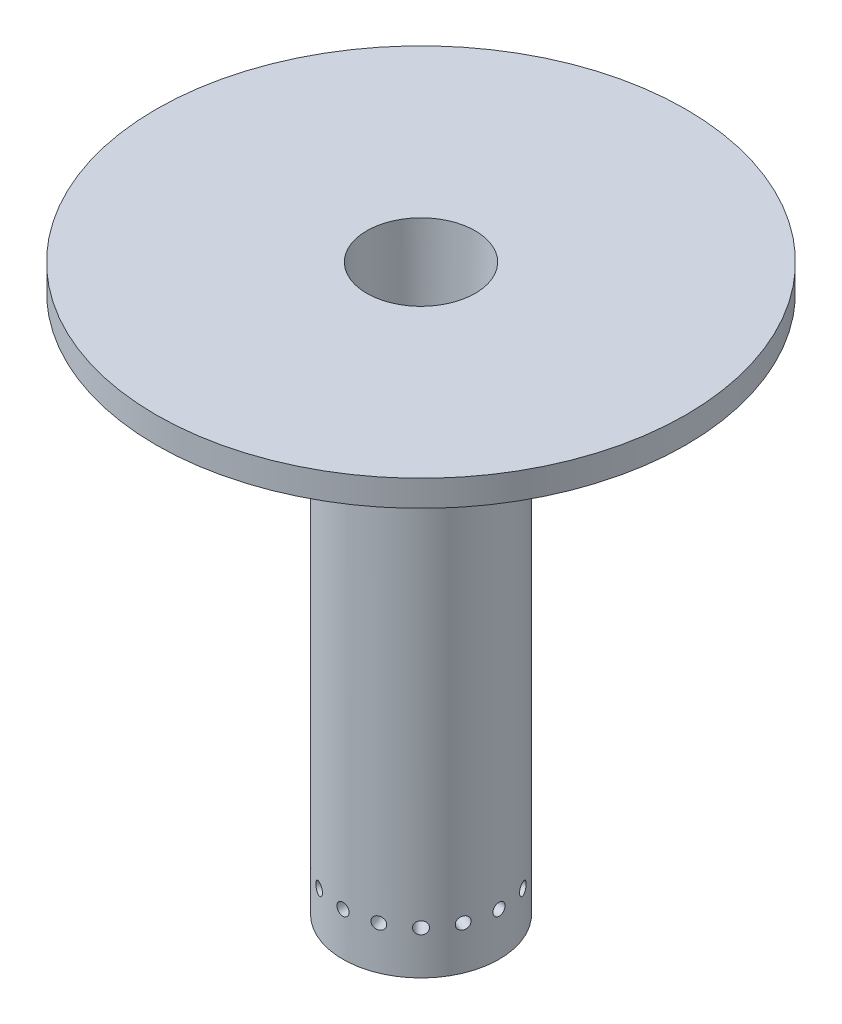
SolidWorks part; units mm, degrees
ref_plane "Front Plane" through (0, 0, 0) normal (0, 0, 1) x (1, 0, 0)
ref_plane "Top Plane" through (0, 0, 0) normal (0, 1, 0) x (1, 0, 0)
ref_plane "Right Plane" through (0, 0, 0) normal (1, 0, 0) x (0, 0, -1)
sketch "Sketch1" plane through (0, 0, 0) normal (0, 0, 1) x (1, 0, 0)
  line L0 (0, 0) -> (-30.48, 0)
  line L1 (-30.48, 0) -> (-30.48, -3)
  line L2 (-30.48, -3) -> (-17.78, -3)
  line L3 (-17.78, -3) -> (-17.78, -8)
  line L4 (-17.78, -8) -> (-9, -8)
  line L5 (-9, -8) -> (-9, -65)
  line L6 (-9, -65) -> (0, -65)
  line L7 (0, -65) -> (0, 0)
  dimension "D1" = 30.48
  dimension "D2" = 12.7
  dimension "D3" = 5
  dimension "D4" = 65
  dimension "D5" = 3
  dimension "D6" = 9
revolve "Revolve1" add sketch "Sketch1" angle 360 about L7
hole_wizard "1/4 NPT Tapped Hole1" positions "Sketch2" profile "Sketch4" size "1/4" standard "ANSI Inch"
sketch "Sketch2" plane through (0, 0, 0) normal (0, 1, 0) x (1, 0, 0)
  point P0 (0, 0)
sketch "Sketch4" plane through (0, 0, 0) normal (1, 0, 0) x (0, 0, 1)
  line L0 (0, 0) -> (0, 40.4123)
  line L1 (5.5626, 37.07) -> (0, 40.4123)
  line L2 (-5.5626, 37.07) -> (0, 40.4123) construction
  line L3 (5.5626, 37.07) -> (5.5626, 10.02)
  line L4 (5.5626, 10.02) -> (5.9437, 10.02)
  line L5 (5.9437, 10.02) -> (6.2437, 0)
  line L6 (-5.9437, 10.02) -> (-6.2437, 0) construction
  line L7 (6.2437, 0) -> (0, 0)
  line L8 (0, -6.35) -> (0, 107.95) construction
  line L11 (-5.5626, 10.02) -> (-5.9437, 10.02) construction
  dimension "Tap Drill Dia." = 11.1252
  dimension "Tap Drill Depth" = 37.07
  dimension "Thread Dia." = 12.4874
  dimension "Thread Angle" = 3.43
  dimension "Thread Depth" = 10.02
  dimension "Drill Angle" = 118
cosmetic thread "Hole Thread1" parameters "D1"=10.02, "D2"=13.716
hole_wizard "3/8 (0.375) Diameter Hole1" positions "Sketch6" profile "Sketch7" hole size "3/8" standard "ANSI Inch"
sketch "Sketch6" plane through (0, 0, 0) normal (0, 1, 0) x (1, 0, 0)
  point P0 (0, 0)
sketch "Sketch7" plane through (0, 0, 0) normal (1, 0, 0) x (0, 0, 1)
  line L0 (0, 0) -> (0, 63.8616)
  line L1 (0, 63.8616) -> (4.7625, 61)
  line L2 (4.7625, 61) -> (4.7625, 0)
  line L5 (4.7625, 0) -> (0, 0)
  line L10 (0, 63.8616) -> (-4.7625, 61) construction
  line L11 (0, -6.35) -> (0, 107.95) construction
  dimension "Hole Dia." = 9.525
  dimension "Hole Depth" = 61
  dimension "Drill Angle" = 118
ref_plane "Plane1" through (0, 0, 9) normal (0, 0, 1) x (1, 0, 0)
hole_wizard "#54 (0.055) Diameter Hole1" positions "Sketch9" profile "Sketch10" hole size "#54" standard "ANSI Inch"
sketch "Sketch9" plane through (0, 0, 9) normal (0, 0, 1) x (1, 0, 0)
  line L1 (30.48, 0) -> (-30.48, 0) construction
  point P0 (0, -60)
  dimension "D1" = 60
sketch "Sketch10" plane through (0, -60, 9) normal (1, 0, 0) x (0, -1, 0)
  line L0 (0, 0) -> (0, 4.2375)
  line L1 (0, 4.2375) -> (0.6985, 4.2375)
  line L2 (0.6985, 4.2375) -> (0.6985, 0)
  line L5 (0.6985, 0) -> (0, 0)
  line L11 (0, -6.35) -> (0, 107.95) construction
  dimension "Thru Hole Dia." = 1.397
  dimension "Thru Hole Depth" = 4.2375
pattern_circular "CirPattern1" count 16 over 360 about axis through (0, -65, 0) along (0, -1, 0) of "#54 (0.055) Diameter Hole1"
